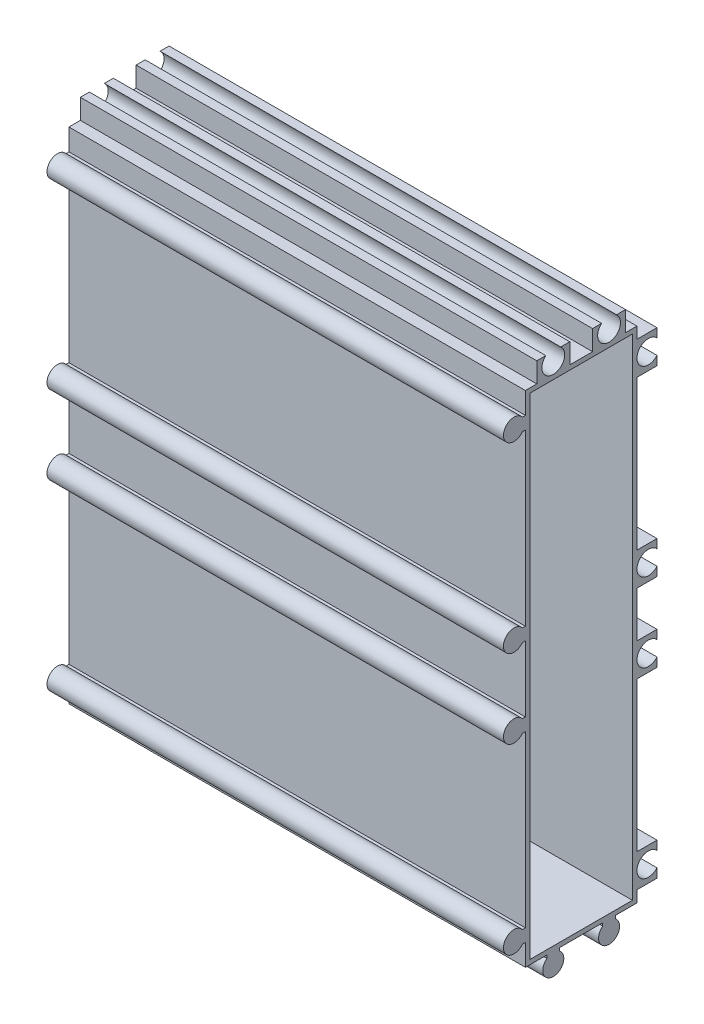
SolidWorks part; units mm, degrees
ref_plane "Спереди" through (0, 0, 0) normal (0, 0, 1) x (1, 0, 0)
ref_plane "Сверху" through (0, 0, 0) normal (0, 1, 0) x (1, 0, 0)
ref_plane "Справа" through (0, 0, 0) normal (1, 0, 0) x (0, 0, -1)
ref_plane "Плоскость4" through (90, 0, 0) normal (1, 0, 0) x (0, 0, -1)
sketch "Эскиз1" plane through (90, 0, 0) normal (1, 0, 0) x (0, 0, -1)
  line L0 (6.75, 40.9062) -> (6.75, 135.75)
  line L1 (6.75, 135.75) -> (-11.5938, 135.75)
  line L2 (-11.5938, 133.25) -> (-11, 133.25)
  line L3 (-11, 133.25) -> (-11, 99.75)
  line L4 (-11, 99.75) -> (-11.5938, 99.75)
  line L5 (-11.5938, 97.25) -> (-11, 97.25)
  line L6 (-11, 97.25) -> (-11, 84.25)
  line L7 (-11, 84.25) -> (-11.5938, 84.25)
  line L8 (-11.5938, 81.75) -> (-11, 81.75)
  line L9 (-11, 81.75) -> (-11, 48.25)
  line L10 (-11, 48.25) -> (-11.5938, 48.25)
  line L11 (-11.5938, 45.75) -> (-11, 45.75)
  line L12 (-11, 45.75) -> (-11, 41.5)
  line L13 (-11, 41.5) -> (-6.75, 41.5)
  line L14 (-6.75, 41.5) -> (-6.75, 40.9062)
  line L15 (-4.25, 40.9062) -> (-4.25, 41.5)
  line L16 (-4.25, 41.5) -> (4.25, 41.5)
  line L17 (4.25, 41.5) -> (4.25, 40.9062)
  arc A0 (-11.5938, 135.75) -> (-11.5938, 133.25) centre (-13.25, 134.5) ccw
  arc A1 (-11.5938, 99.75) -> (-11.5938, 97.25) centre (-13.25, 98.5) ccw
  arc A2 (-11.5938, 84.25) -> (-11.5938, 81.75) centre (-13.25, 83) ccw
  arc A3 (-11.5938, 48.25) -> (-11.5938, 45.75) centre (-13.25, 47) ccw
  arc A4 (-6.75, 40.9062) -> (-4.25, 40.9062) centre (-5.5, 39.25) ccw
  arc A5 (4.25, 40.9062) -> (6.75, 40.9062) centre (5.5, 39.25) ccw
extrude "Бобышка-Вытянуть1" add sketch "Эскиз1" against normal blind 90
sketch "Эскиз2" plane through (0, 135.75, 0) normal (0, 1, 0) x (-1, 0, 0)
  line L0 (-90, -6.75) -> (-90, 11)
  line L1 (-90, 11) -> (0, 11)
  line L2 (0, 11) -> (0, -6.75)
  line L3 (0, -6.75) -> (-90, -6.75)
extrude "Бобышка-Вытянуть2" add sketch "Эскиз2" along normal blind 8.2
sketch "Эскиз3" plane through (0, 0, -6.75) normal (0, 0, -1) x (-1, 0, 0)
  line L0 (-90, 41.5) -> (-90, 143.95)
  line L1 (-90, 143.95) -> (0, 143.95)
  line L2 (0, 143.95) -> (0, 41.5)
  line L3 (0, 41.5) -> (-90, 41.5)
extrude "Бобышка-Вытянуть3" add sketch "Эскиз3" along normal blind 8.2
sketch "Эскиз4" plane through (0, 0, 0) normal (-1, 0, 0) x (0, 0, 1)
  line L0 (-14.95, 41.5) -> (-11, 41.5)
  line L1 (-11, 41.5) -> (-11, 43.75)
  line L2 (-11, 43.75) -> (-14.95, 43.75)
  line L3 (-14.95, 43.75) -> (-14.95, 41.5)
extrude "Вырез-Вытянуть1" cut sketch "Эскиз4" against normal through all
sketch "Эскиз5" plane through (0, 0, 0) normal (-1, 0, 0) x (0, 0, 1)
  line L0 (-14.95, 50.25) -> (-11, 50.25)
  line L1 (-11, 50.25) -> (-11, 79.75)
  line L2 (-11, 79.75) -> (-14.95, 79.75)
  line L3 (-14.95, 79.75) -> (-14.95, 50.25)
extrude "Вырез-Вытянуть2" cut sketch "Эскиз5" against normal through all
sketch "Эскиз6" plane through (0, 0, 0) normal (-1, 0, 0) x (0, 0, 1)
  line L0 (-14.95, 86.25) -> (-11, 86.25)
  line L1 (-11, 86.25) -> (-11, 95.25)
  line L2 (-11, 95.25) -> (-14.95, 95.25)
  line L3 (-14.95, 95.25) -> (-14.95, 86.25)
extrude "Вырез-Вытянуть3" cut sketch "Эскиз6" against normal through all
sketch "Эскиз7" plane through (0, 0, 0) normal (-1, 0, 0) x (0, 0, 1)
  line L0 (-14.95, 101.75) -> (-11, 101.75)
  line L1 (-11, 101.75) -> (-11, 131.25)
  line L2 (-11, 131.25) -> (-14.95, 131.25)
  line L3 (-14.95, 131.25) -> (-14.95, 101.75)
extrude "Вырез-Вытянуть4" cut sketch "Эскиз7" against normal through all
sketch "Эскиз8" plane through (0, 0, 0) normal (-1, 0, 0) x (0, 0, 1)
  line L0 (-14.95, 143.95) -> (-14.95, 137.75)
  line L1 (-14.95, 137.75) -> (-11, 137.75)
  line L2 (-11, 137.75) -> (-11, 143.95)
  line L3 (-11, 143.95) -> (-14.95, 143.95)
extrude "Вырез-Вытянуть5" cut sketch "Эскиз8" against normal through all
sketch "Эскиз9" plane through (0, 0, 0) normal (-1, 0, 0) x (0, 0, 1)
  line L0 (-11, 143.95) -> (-11, 140)
  line L1 (-11, 140) -> (-8.75, 140)
  line L2 (-8.75, 140) -> (-8.75, 143.95)
  line L3 (-8.75, 143.95) -> (-11, 143.95)
extrude "Вырез-Вытянуть6" cut sketch "Эскиз9" against normal through all
sketch "Эскиз10" plane through (0, 0, 0) normal (-1, 0, 0) x (0, 0, 1)
  line L0 (-2.25, 143.95) -> (-2.25, 140)
  line L1 (-2.25, 140) -> (2.25, 140)
  line L2 (2.25, 140) -> (2.25, 143.95)
  line L3 (2.25, 143.95) -> (-2.25, 143.95)
extrude "Вырез-Вытянуть7" cut sketch "Эскиз10" against normal through all
sketch "Эскиз11" plane through (0, 0, 0) normal (-1, 0, 0) x (0, 0, 1)
  line L0 (11, 143.95) -> (8.75, 143.95)
  line L1 (8.75, 143.95) -> (8.75, 140)
  line L2 (8.75, 140) -> (11, 140)
  line L3 (11, 140) -> (11, 143.95)
extrude "Вырез-Вытянуть8" cut sketch "Эскиз11" against normal through all
sketch "Эскиз12" plane through (90, 0, 0) normal (1, 0, 0) x (0, 0, -1)
  line L0 (10.1, 139.1) -> (-10.1, 139.1)
  line L1 (-10.1, 139.1) -> (-10.1, 42.4)
  line L2 (-10.1, 42.4) -> (10.1, 42.4)
  line L3 (10.1, 42.4) -> (10.1, 139.1)
extrude "Вырез-Вытянуть9" cut sketch "Эскиз12" against normal blind 86
hole_wizard "Диаметр отверстия Ø8.3 (8.3)1" positions "Эскиз14" profile "Эскиз13" hole size "Ø8.3" standard "Ansi Metric"
sketch "Эскиз14" plane through (0, 0, 0) normal (-1, 0, 0) x (0, 0, 1)
  point P0 (0, 90)
sketch "Эскиз13" plane through (0, 90, 0) normal (0, 1, 0) x (0, 0, 1)
  line L0 (0, 0) -> (0, 3.2)
  line L1 (0, 3.2) -> (4.15, 3.2)
  line L2 (4.15, 3.2) -> (4.15, 0)
  line L5 (4.15, 0) -> (0, 0)
  line L10 (0, 3.2) -> (-4.15, 3.2) construction
  line L11 (0, -6.35) -> (0, 107.95) construction
  dimension "Диаметр отверстия" = 8.3
  dimension "Глубина отверстия" = 3.2
  dimension "Угол заточки сверла" = 180
hole_wizard "Диаметр отверстия Ø4.5 (4.5)1" positions "Эскиз16" profile "Эскиз15" hole size "Ø4.5" standard "Ansi Metric"
sketch "Эскиз16" plane through (0, 0, 0) normal (-1, 0, 0) x (0, 0, 1)
  point P0 (-13.25, 47)
  point P1 (-13.25, 83)
  point P2 (-13.25, 98.5)
  point P3 (-13.25, 134.5)
  point P4 (-5.5, 142.25)
  point P5 (5.5, 142.25)
sketch "Эскиз15" plane through (0, 47, -13.25) normal (0, 1, 0) x (0, 0, 1)
  line L0 (0, 0) -> (0, 90)
  line L1 (0, 90) -> (2.25, 90)
  line L2 (2.25, 90) -> (2.25, 0)
  line L5 (2.25, 0) -> (0, 0)
  line L11 (0, -6.35) -> (0, 107.95) construction
  dimension "Диаметр сквозного отверстия" = 4.5
  dimension "Глубина сквозного отверстия" = 90
hole_wizard "Диаметр отверстия Ø2.5 (2.5)1" positions "Эскиз18" profile "Эскиз17" hole size "Ø2.5" standard "Ansi Metric"
sketch "Эскиз18" plane through (90, 0, 0) normal (1, 0, 0) x (0, 0, -1)
  point P0 (-13.25, 98.5)
  point P1 (-13.25, 134.5)
  point P2 (-13.25, 47)
  point P3 (-13.25, 83)
  point P4 (5.5, 39.25)
  point P5 (-5.5, 39.25)
sketch "Эскиз17" plane through (90, 98.5, 13.25) normal (0, 1, 0) x (0, 0, -1)
  line L0 (0, 0) -> (0, 90)
  line L1 (0, 90) -> (1.25, 90)
  line L2 (1.25, 90) -> (1.25, 0)
  line L5 (1.25, 0) -> (0, 0)
  line L11 (0, -6.35) -> (0, 107.95) construction
  dimension "Диаметр сквозного отверстия" = 2.5
  dimension "Глубина сквозного отверстия" = 90
sketch "Эскиз19" plane through (0, 0, 0) normal (-1, 0, 0) x (0, 0, 1)
  circle A0 centre (0, 90) radius 4.5031
extrude "Бобышка-Вытянуть4" add sketch "Эскиз19" against normal blind 3
sketch "Эскиз20" plane through (90, 0, 0) normal (1, 0, 0) x (0, 0, -1)
  circle A0 centre (-13.25, 134.5) radius 1.6499
  circle A1 centre (-13.25, 98.5) radius 1.6606
  circle A2 centre (-13.25, 83) radius 1.4307
  circle A3 centre (-13.25, 47) radius 1.5733
  circle A4 centre (-5.5, 39.25) radius 1.502
  circle A5 centre (5.5, 39.25) radius 1.538
extrude "Бобышка-Вытянуть5" add sketch "Эскиз20" against normal blind 90
